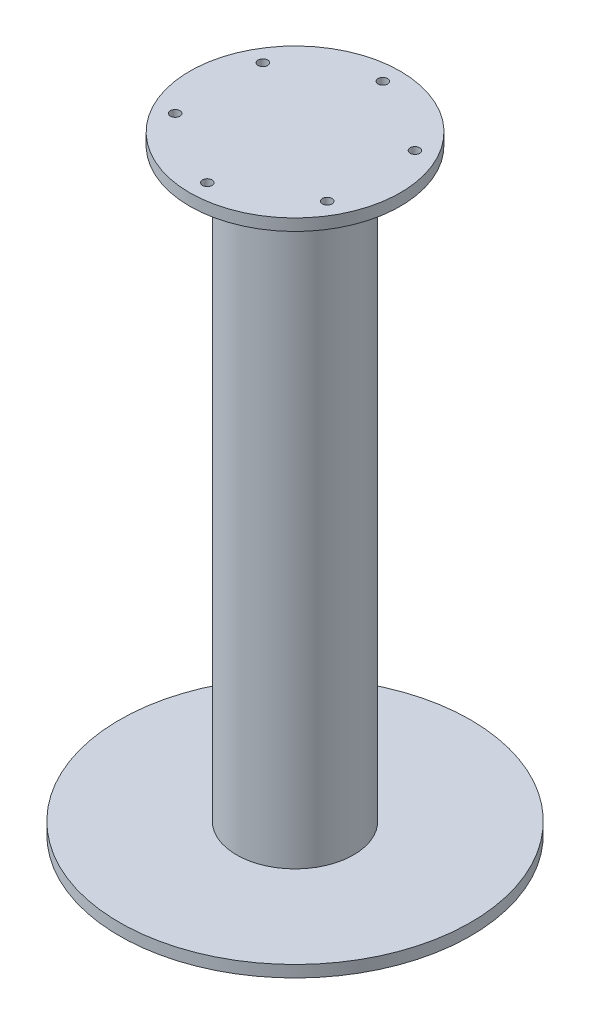
SolidWorks part; units mm, degrees
ref_plane "前视基准面" through (0, 0, 0) normal (0, 0, 1) x (1, 0, 0)
ref_plane "上视基准面" through (0, 0, 0) normal (0, 1, 0) x (1, 0, 0)
ref_plane "右视基准面" through (0, 0, 0) normal (1, 0, 0) x (0, 0, -1)
sketch "草图1" plane through (0, 0, 0) normal (0, 1, 0) x (1, 0, 0)
  line L0 (0, 43.5816) -> (0, -48.938) construction
  circle A0 centre (0, 0) radius 75 construction
  circle A1 centre (0, -75) radius 4.1
  circle A9 centre (0, 0) radius 90
  circle A10 centre (-64.9519, -37.5) radius 4.1
  circle A11 centre (-64.9519, 37.5) radius 4.1
  circle A12 centre (0, 75) radius 4.1
  circle A13 centre (64.9519, 37.5) radius 4.1
  circle A14 centre (64.9519, -37.5) radius 4.1
  point P21 (0, 0)
  point P24 (0, 0)
  dimension "D1" = 150
  dimension "D2" = 8.2
  dimension "D4" = 180
  dimension "D3" = 6
extrude "凸台-拉伸1" add sketch "草图1" along normal blind 10
sketch "草图2" plane through (0, 0, 0) normal (0, -1, 0) x (1, 0, 0)
  circle A0 centre (0, 0) radius 50
  dimension "D1" = 100
extrude "凸台-拉伸2" add sketch "草图2" along normal blind 500
sketch "草图3" plane through (0, -500, 0) normal (0, -1, 0) x (1, 0, 0)
  circle A0 centre (0, 0) radius 150
  dimension "D1" = 300
extrude "凸台-拉伸3" add sketch "草图3" along normal blind 10 contours A0
